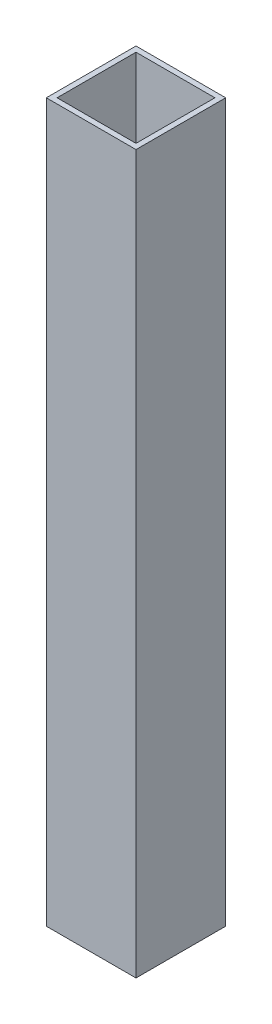
SolidWorks part; units mm, degrees
ref_plane "Front Plane" through (0, 0, 0) normal (0, 0, 1) x (1, 0, 0)
ref_plane "Top Plane" through (0, 0, 0) normal (0, 1, 0) x (1, 0, 0)
ref_plane "Right Plane" through (0, 0, 0) normal (1, 0, 0) x (0, 0, -1)
sketch "Sketch1" plane through (0, 0, 0) normal (0, 1, 0) x (1, 0, 0)
  line L0 (-26.6278, 1.8372) -> (-14.1278, -10.6628) construction
  line L1 (-26.6278, 1.8372) -> (-14.1278, 1.8372)
  line L2 (-26.6278, 1.8372) -> (-26.6278, -10.6628)
  line L3 (-26.6278, -10.6628) -> (-14.1278, -10.6628)
  line L4 (-14.1278, 1.8372) -> (-14.1278, -10.6628)
  line L5 (-26.6278, -10.6628) -> (-14.1278, 1.8372) construction
  line L7 (-25.8778, 1.0872) -> (-14.8778, 1.0872)
  line L8 (-25.8778, 1.0872) -> (-25.8778, -9.9128)
  line L9 (-25.8778, -9.9128) -> (-14.8778, -9.9128)
  line L10 (-14.8778, 1.0872) -> (-14.8778, -9.9128)
  line L11 (-25.8778, 1.0872) -> (-14.8778, -9.9128) construction
  line L12 (-25.8778, -9.9128) -> (-14.8778, 1.0872) construction
  point P4 (-20.3778, -4.4128)
extrude "Boss-Extrude3" add sketch "Sketch1" along normal blind 100
